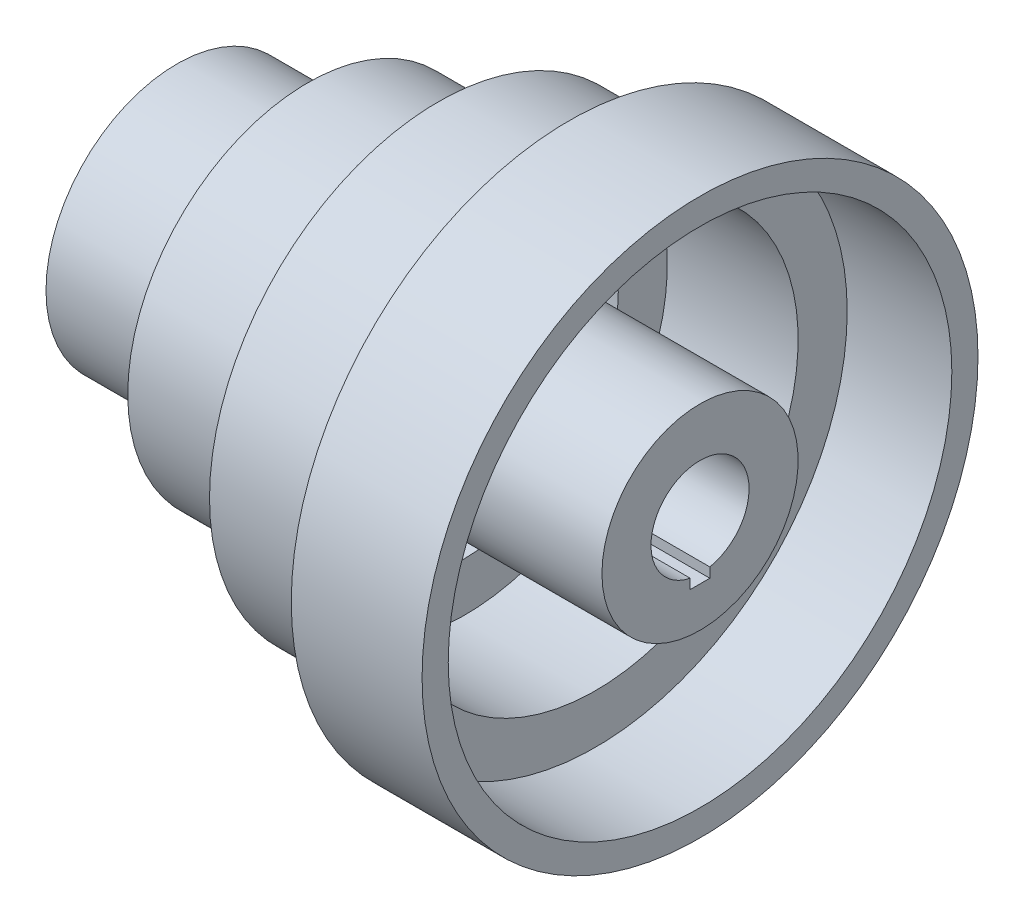
SolidWorks part; units mm, degrees
ref_plane "Front Plane" through (0, 0, 0) normal (0, 0, 1) x (1, 0, 0)
ref_plane "Top Plane" through (0, 0, 0) normal (0, 1, 0) x (1, 0, 0)
ref_plane "Right Plane" through (0, 0, 0) normal (1, 0, 0) x (0, 0, -1)
sketch "Sketch1" plane through (0, 0, 0) normal (0, 1, 0) x (1, 0, 0)
  line L0 (0, 15) -> (0, 40)
  line L1 (0, 40) -> (40, 40)
  line L2 (40, 40) -> (40, 55)
  line L3 (40, 55) -> (80, 55)
  line L4 (80, 55) -> (80, 70)
  line L5 (80, 70) -> (120, 70)
  line L6 (120, 70) -> (120, 85)
  line L7 (120, 85) -> (160, 85)
  line L8 (-116.688, 0) -> (292.556, 0) construction
  line L9 (160, 85) -> (160, 77)
  line L10 (160, 77) -> (128, 77)
  line L11 (128, 77) -> (128, 62)
  line L12 (128, 62) -> (88, 62)
  line L13 (88, 62) -> (88, 47)
  line L14 (88, 47) -> (48, 47)
  line L15 (48, 47) -> (48, 30)
  line L16 (48, 30) -> (160, 30)
  line L17 (0, 15) -> (160, 15)
  line L18 (160, 30) -> (160, 15)
  dimension "D1" = 40
  dimension "D2" = 40
  dimension "D3" = 40
  dimension "D4" = 40
  dimension "D7" = 55
  dimension "D8" = 70
  dimension "D9" = 8
  dimension "D10" = 8
  dimension "D11" = 8
  dimension "D12" = 8
  dimension "D13" = 8
  dimension "D14" = 8
  dimension "D15" = 30
  dimension "D16" = 15
revolve "Revolve1" add sketch "Sketch1" angle 360 about L8
sketch "Sketch2" plane through (0, 0, 0) normal (-1, 0, 0) x (0, 0, 1)
  line L0 (-3, -14.6969) -> (-3, -17.6969)
  line L1 (-3, -17.6969) -> (3, -17.6969)
  line L2 (3, -17.6969) -> (3, -14.6969)
  circle A0 centre (0, 0) radius 15 construction
  arc A1 (-3, -14.6969) -> (3, -14.6969) centre (0, 0) ccw
  dimension "D1" = 6
  dimension "D2" = 3
  dimension "D3" = 3
extrude "Cut-Extrude1" cut sketch "Sketch2" against normal up to next
